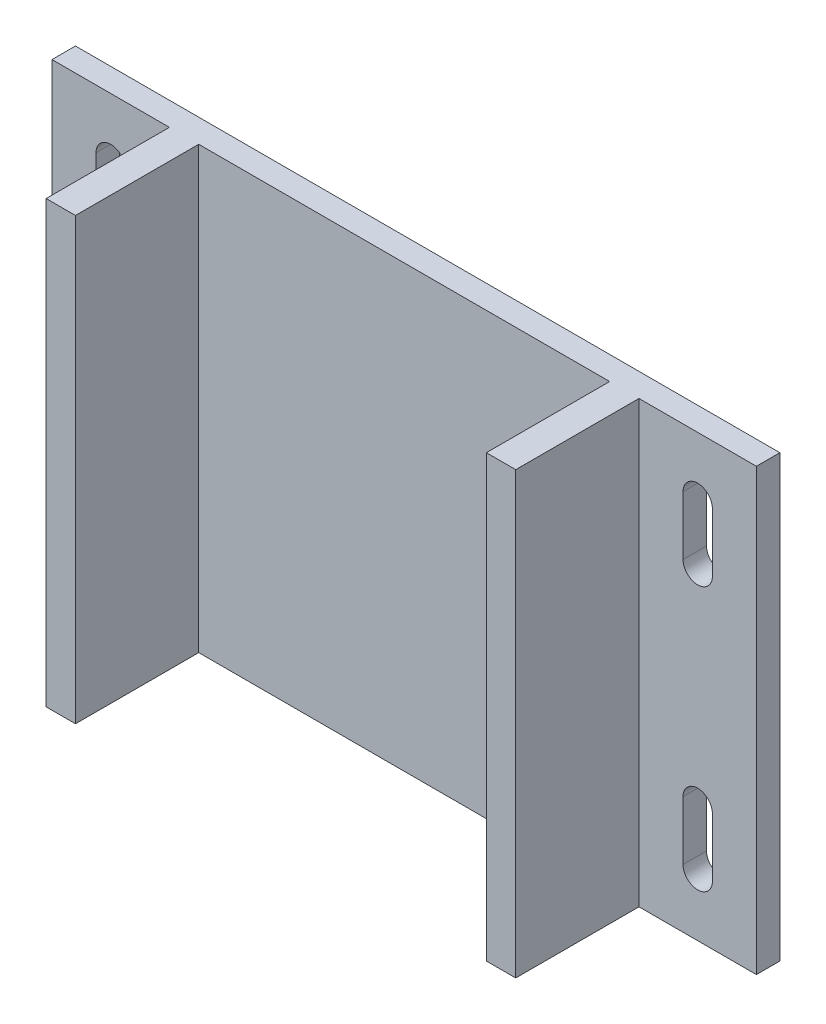
SolidWorks part; units mm, degrees
ref_plane "前视基准面" through (0, 0, 0) normal (0, 0, 1) x (1, 0, 0)
ref_plane "上视基准面" through (0, 0, 0) normal (0, 1, 0) x (1, 0, 0)
ref_plane "右视基准面" through (0, 0, 0) normal (1, 0, 0) x (0, 0, -1)
sketch "草图1" plane through (0, 0, 0) normal (0, 0, 1) x (1, 0, 0)
  line L1 (0, 0) -> (120, 0)
  line L2 (0, 0) -> (0, 75)
  line L3 (0, 75) -> (120, 75)
  line L4 (120, 0) -> (120, 75)
  dimension "D1" = 120
  dimension "D2" = 75
extrude "凸台-拉伸1" add sketch "草图1" along normal blind 4
sketch "草图2" plane through (0, 0, 4) normal (0, 0, 1) x (1, 0, 0)
  line L0 (0, 0) -> (120, 0) construction
  line L1 (20, 0) -> (25, 0)
  line L2 (20, 0) -> (20, 75)
  line L3 (20, 75) -> (25, 75)
  line L4 (25, 0) -> (25, 75)
  line L5 (120, 75) -> (0, 75) construction
  line L6 (120, 0) -> (120, 75) construction
  line L7 (95, 0) -> (100, 0)
  line L8 (95, 0) -> (95, 75)
  line L9 (95, 75) -> (100, 75)
  line L10 (100, 0) -> (100, 75)
  dimension "D1" = 5
  dimension "D2" = 5
  dimension "D3" = 20
  dimension "D4" = 20
extrude "凸台-拉伸2" add sketch "草图2" along normal blind 21
sketch "草图3" plane through (0, 0, 0) normal (0, 0, -1) x (-1, 0, 0)
  line L0 (-60, 75) -> (-60, 0) construction
  line L1 (-120, 75) -> (0, 75) construction
  line L2 (0, 0) -> (-120, 0) construction
  line L3 (-112.5, 65) -> (-112.5, 55)
  line L4 (-107.5, 65) -> (-107.5, 55)
  line L7 (-120, 0) -> (-120, 75) construction
  line L8 (-120, 37.5) -> (0, 37.5) construction
  line L10 (0, 75) -> (0, 0) construction
  line L11 (-107.5, 10) -> (-107.5, 20)
  line L12 (-112.5, 10) -> (-112.5, 20)
  line L13 (-7.5, 10) -> (-7.5, 20)
  line L14 (-12.5, 10) -> (-12.5, 20)
  line L15 (-12.5, 65) -> (-12.5, 55)
  line L16 (-7.5, 65) -> (-7.5, 55)
  arc A0 (-107.5, 65) -> (-112.5, 65) centre (-110, 65) ccw
  arc A1 (-112.5, 55) -> (-107.5, 55) centre (-110, 55) ccw
  arc A2 (-112.5, 20) -> (-107.5, 20) centre (-110, 20) cw
  arc A3 (-107.5, 10) -> (-112.5, 10) centre (-110, 10) cw
  arc A4 (-12.5, 10) -> (-7.5, 10) centre (-10, 10) ccw
  arc A5 (-7.5, 20) -> (-12.5, 20) centre (-10, 20) ccw
  arc A6 (-7.5, 55) -> (-12.5, 55) centre (-10, 55) cw
  arc A7 (-12.5, 65) -> (-7.5, 65) centre (-10, 65) cw
  dimension "D1" = 5
  dimension "D2" = 5
  dimension "D3" = 10
  dimension "D4" = 10
  dimension "D5" = 10
extrude "切除-拉伸1" cut sketch "草图3" against normal through all
